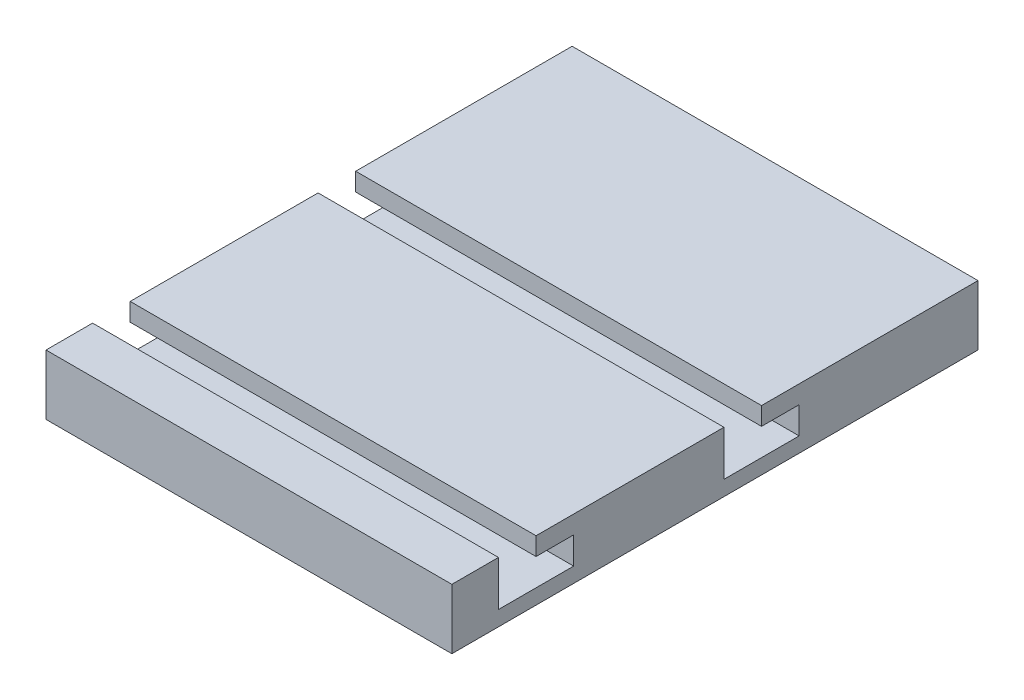
SolidWorks part; units mm, degrees
ref_plane "Front Plane" through (0, 0, 0) normal (1, 0, 0) x (0, 1, 0)
ref_plane "Top Plane" through (0, 0, 0) normal (0, 0, 1) x (0, 1, 0)
ref_plane "Right Plane" through (0, 0, 0) normal (0, 1, 0) x (-1, 0, 0)
sketch "Sketch1" plane through (0, 0, 0) normal (0, 1, 0) x (-1, 0, 0)
  line L1 (0, 0) -> (68.58, 0)
  line L2 (0, 0) -> (0, 88.9)
  line L3 (0, 88.9) -> (68.58, 88.9)
  line L4 (68.58, 0) -> (68.58, 88.9)
  dimension "D1" = 68.58
  dimension "D2" = 88.9
extrude "Boss-Extrude1" add sketch "Sketch1" along normal blind 2.54
sketch "Sketch2" plane through (0, 2.54, 0) normal (0, 1, 0) x (-1, 0, 0)
  line L0 (0, 88.9) -> (0, 0) construction
  line L1 (0, 64.516) -> (68.58, 64.516)
  line L2 (0, 64.516) -> (0, 69.596)
  line L3 (0, 69.596) -> (68.58, 69.596)
  line L4 (68.58, 64.516) -> (68.58, 69.596)
  line L5 (68.58, 0) -> (68.58, 88.9) construction
  line L6 (68.58, 88.9) -> (0, 88.9) construction
  line L7 (0, 26.416) -> (68.58, 26.416)
  line L8 (0, 26.416) -> (0, 31.496)
  line L9 (0, 31.496) -> (68.58, 31.496)
  line L10 (68.58, 26.416) -> (68.58, 31.496)
  dimension "D1" = 5.08
  dimension "D2" = 19.304
  dimension "D3" = 38.1
extrude "Boss-Extrude2" add sketch "Sketch2" along normal blind 7.62
sketch "Sketch3" plane through (0, 0, 31.496) normal (0, 0, 1) x (1, 0, 0)
  line L0 (-68.58, 10.16) -> (-68.58, 2.54) construction
  line L1 (-68.58, 7.112) -> (0, 7.112)
  line L2 (-68.58, 7.112) -> (-68.58, 10.16)
  line L3 (-68.58, 10.16) -> (0, 10.16)
  line L4 (0, 7.112) -> (0, 10.16)
  dimension "D1" = 3.048
extrude "Boss-Extrude3" add sketch "Sketch3" along normal blind 6.35
sketch "Sketch4" plane through (0, 0, 69.596) normal (0, 0, 1) x (1, 0, 0)
  line L0 (-68.58, 10.16) -> (-68.58, 2.54) construction
  line L1 (-68.58, 7.112) -> (0, 7.112)
  line L2 (-68.58, 7.112) -> (-68.58, 10.16)
  line L3 (-68.58, 10.16) -> (0, 10.16)
  line L4 (0, 7.112) -> (0, 10.16)
  dimension "D1" = 3.048
extrude "Boss-Extrude4" add sketch "Sketch4" along normal blind 6.35
sketch "Sketch5" plane through (0, 2.54, 0) normal (0, 1, 0) x (-1, 0, 0)
  line L0 (0, 64.516) -> (0, 31.496) construction
  line L1 (0, 0) -> (68.58, 0)
  line L2 (0, 0) -> (0, 26.416)
  line L3 (0, 26.416) -> (68.58, 26.416)
  line L4 (68.58, 0) -> (68.58, 26.416)
  line L5 (0, 42.926) -> (68.58, 42.926)
  line L6 (0, 42.926) -> (0, 64.516)
  line L7 (0, 64.516) -> (68.58, 64.516)
  line L8 (68.58, 42.926) -> (68.58, 64.516)
  line L9 (0, 88.9) -> (0, 69.596) construction
  line L10 (0, 81.026) -> (68.58, 81.026)
  line L11 (0, 81.026) -> (0, 88.9)
  line L12 (0, 88.9) -> (68.58, 88.9)
  line L13 (68.58, 81.026) -> (68.58, 88.9)
  line L14 (0, 75.946) -> (68.58, 75.946) construction
  line L15 (0, 37.846) -> (68.58, 37.846) construction
  dimension "D1" = 5.08
  dimension "D2" = 5.08
extrude "Boss-Extrude5" add sketch "Sketch5" along normal blind 7.62
sketch "Sketch6" plane through (0, 0, 0) normal (1, 0, 0) x (0, 1, 0)
  line L0 (10.16, 37.846) -> (10.16, 0) construction
  line L1 (2.54, 69.596) -> (7.112, 69.596)
  line L2 (2.54, 69.596) -> (2.54, 68.326)
  line L3 (2.54, 68.326) -> (7.112, 68.326)
  line L4 (7.112, 69.596) -> (7.112, 68.326)
  line L5 (2.54, 31.496) -> (7.112, 31.496)
  line L6 (2.54, 31.496) -> (2.54, 30.226)
  line L7 (2.54, 30.226) -> (7.112, 30.226)
  line L8 (7.112, 31.496) -> (7.112, 30.226)
  line L9 (7.112, 37.846) -> (10.16, 37.846)
  line L10 (7.112, 37.846) -> (7.112, 36.576)
  line L11 (7.112, 36.576) -> (10.16, 36.576)
  line L12 (10.16, 37.846) -> (10.16, 36.576)
  line L13 (10.16, 75.946) -> (10.16, 42.926) construction
  line L14 (7.112, 75.946) -> (10.16, 75.946)
  line L15 (7.112, 75.946) -> (7.112, 74.676)
  line L16 (7.112, 74.676) -> (10.16, 74.676)
  line L17 (10.16, 75.946) -> (10.16, 74.676)
  line L18 (7.112, 75.946) -> (7.112, 69.596) construction
  point P24 (7.112, 30.861)
  dimension "D1" = 1.27
  dimension "D2" = 1.27
extrude "Cut-Extrude1" cut sketch "Sketch6" against normal through all
